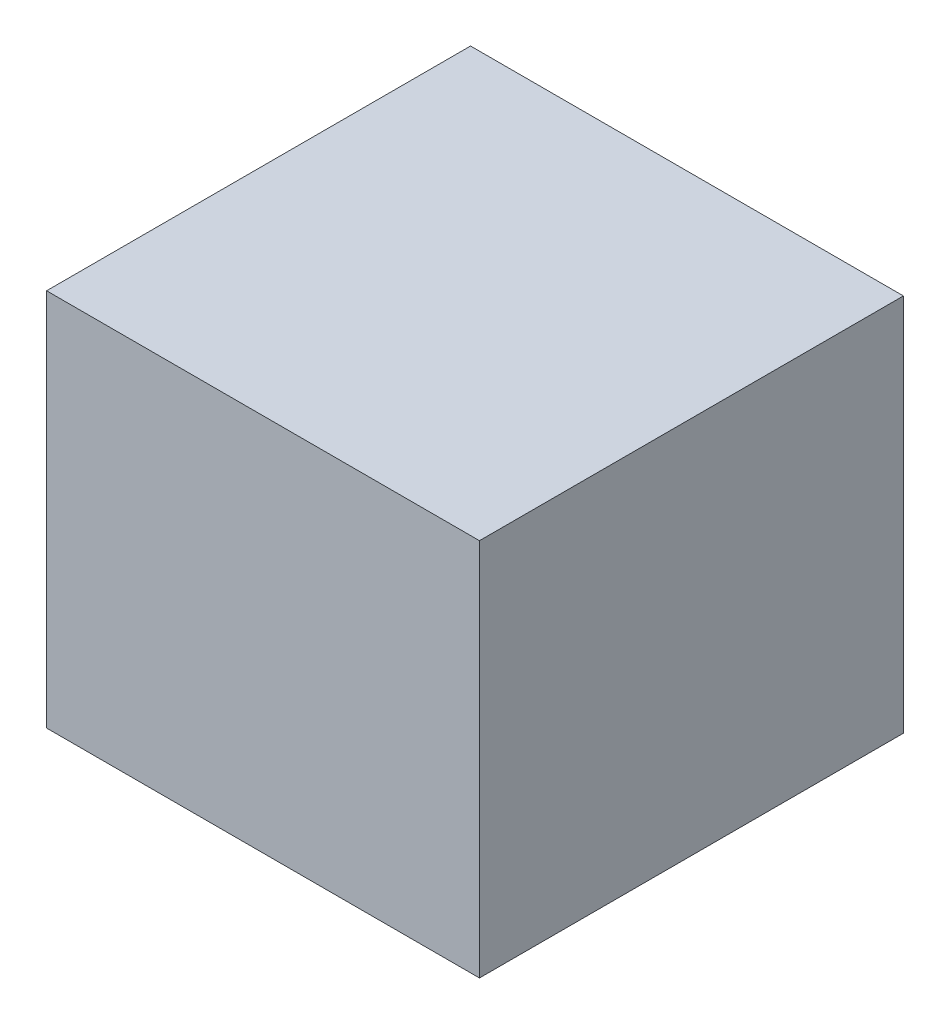
SolidWorks part; units mm, degrees
ref_plane "Front Plane" through (0, 0, 0) normal (0, 0, 1) x (1, 0, 0)
ref_plane "Top Plane" through (0, 0, 0) normal (0, 1, 0) x (1, 0, 0)
ref_plane "Right Plane" through (0, 0, 0) normal (1, 0, 0) x (0, 0, -1)
sketch "Sketch1" plane through (-13.7935, 0, 0) normal (1, 0, 0) x (0, 0, -1)
  line L1 (-27.0759, -29.1749) -> (-26.9437, -29.1749)
  line L2 (-27.0759, -29.1749) -> (-27.0759, -29.0567)
  line L3 (-27.0759, -29.0567) -> (-26.9437, -29.0567)
  line L4 (-26.9437, -29.1749) -> (-26.9437, -29.0567)
extrude "Boss-Extrude1" add sketch "Sketch1" along normal blind 0.135
